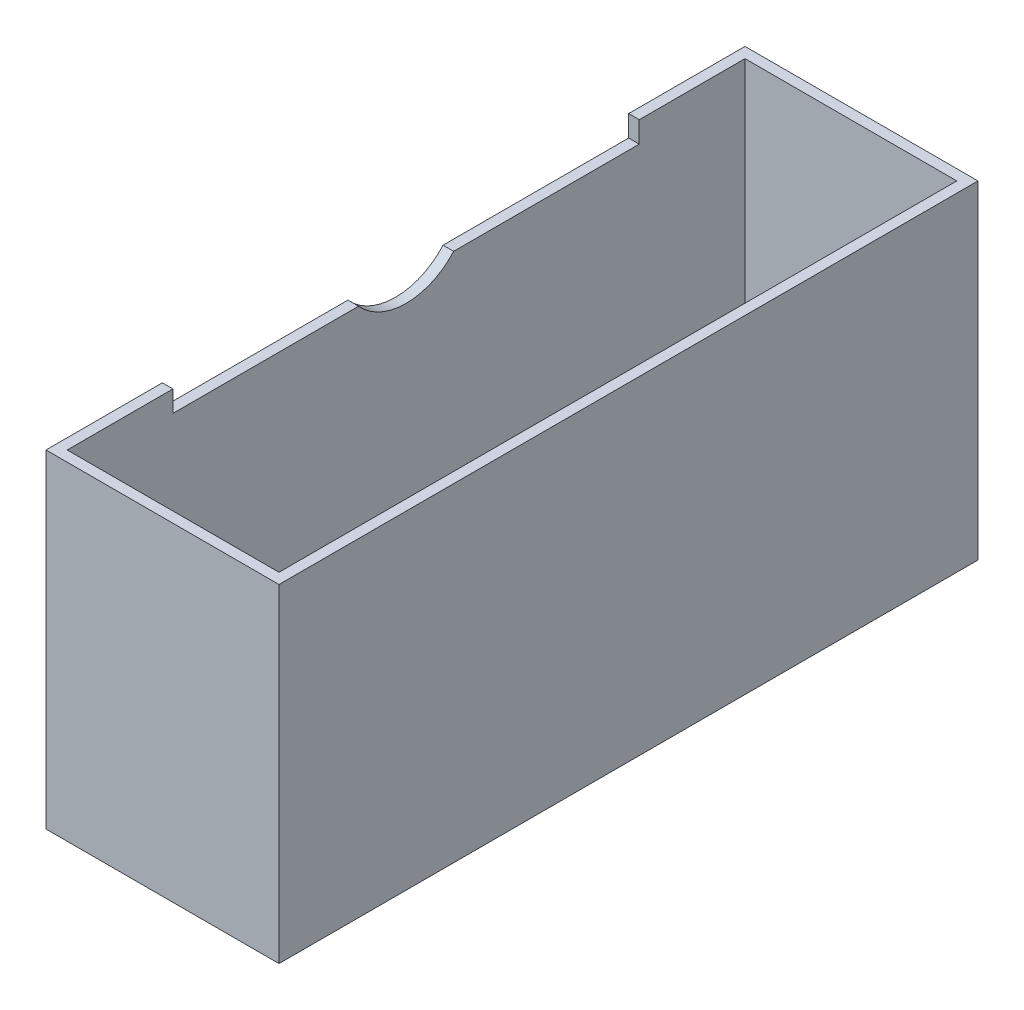
SolidWorks part; units mm, degrees
ref_plane "Front Plane" through (0, 0, 0) normal (0, 0, 1) x (1, 0, 0)
ref_plane "Top Plane" through (0, 0, 0) normal (0, 1, 0) x (1, 0, 0)
ref_plane "Right Plane" through (0, 0, 0) normal (1, 0, 0) x (0, 0, -1)
sketch "Sketch1" plane through (0, 0, 0) normal (0, 1, 0) x (1, 0, 0)
  line L1 (-34.925, 104.775) -> (34.925, 104.775)
  line L2 (-34.925, 104.775) -> (-34.925, -104.775)
  line L3 (-34.925, -104.775) -> (34.925, -104.775)
  line L4 (34.925, 104.775) -> (34.925, -104.775)
  line L5 (-34.925, 104.775) -> (34.925, -104.775) construction
  line L6 (-34.925, -104.775) -> (34.925, 104.775) construction
  point P0 (0, 0)
  dimension "D1" = 209.55
  dimension "D2" = 69.85
extrude "Boss-Extrude1" add sketch "Sketch1" along normal blind 98.425
sketch "Sketch2" plane through (0, 98.425, 0) normal (0, 1, 0) x (1, 0, 0)
  line L0 (34.925, 104.775) -> (-34.925, 104.775) construction
  line L1 (-31.75, -101.6) -> (31.75, -101.6)
  line L2 (-31.75, -101.6) -> (-31.75, 101.6)
  line L3 (-31.75, 101.6) -> (31.75, 101.6)
  line L4 (31.75, -101.6) -> (31.75, 101.6)
  line L5 (-31.75, -101.6) -> (31.75, 101.6) construction
  line L6 (-31.75, 101.6) -> (31.75, -101.6) construction
  line L7 (-34.925, 104.775) -> (-34.925, -104.775) construction
  point P0 (0, 0)
  dimension "D1" = 3.175
  dimension "D2" = 3.175
extrude "Cut-Extrude1" cut sketch "Sketch2" against normal offset from surface (95.25 mm away) 3.175 up to face at (0, 0, 0)
sketch "Sketch3" plane through (-34.925, 0, 0) normal (-1, 0, 0) x (0, 0, 1)
  line L0 (0, 1.454) -> (0, 98.425) construction
  line L1 (-104.775, 98.425) -> (104.775, 98.425) construction
  line L2 (-14.246, 92.075) -> (-69.897, 92.075) construction
  line L5 (-69.897, 92.075) -> (-69.897, 98.425) construction
  line L11 (-69.897, 98.425) -> (-69.897, 178.107)
  line L12 (-69.897, 178.107) -> (69.897, 178.107)
  line L13 (69.897, 178.107) -> (69.897, 98.425)
  line L23 (-69.897, 98.425) -> (-19.097, 98.425) construction
  line L24 (69.897, 92.075) -> (69.897, 98.425) construction
  line L26 (14.246, 92.075) -> (69.897, 92.075) construction
  line L27 (0, 104.7223) -> (0, 85.6723) construction
  line L28 (-69.897, 98.425) -> (-69.897, 92.075)
  line L29 (-69.897, 92.075) -> (-14.246, 92.075)
  line L30 (14.246, 92.075) -> (69.897, 92.075)
  line L31 (69.897, 92.075) -> (69.897, 98.425)
  arc A6 (-14.246, 92.075) -> (14.246, 92.075) centre (0, 104.7223) ccw construction
  arc A7 (-14.246, 92.075) -> (14.246, 92.075) centre (0, 104.7223) ccw
  dimension "D1" = 19.05
  dimension "D2" = 12.7527
  dimension "D7" = 6.35
  dimension "D8" = 55.651
extrude "Cut-Extrude2" cut sketch "Sketch3" against normal up to surface (3.175 mm away) up to face at (-31.75, 50.8, 0)
